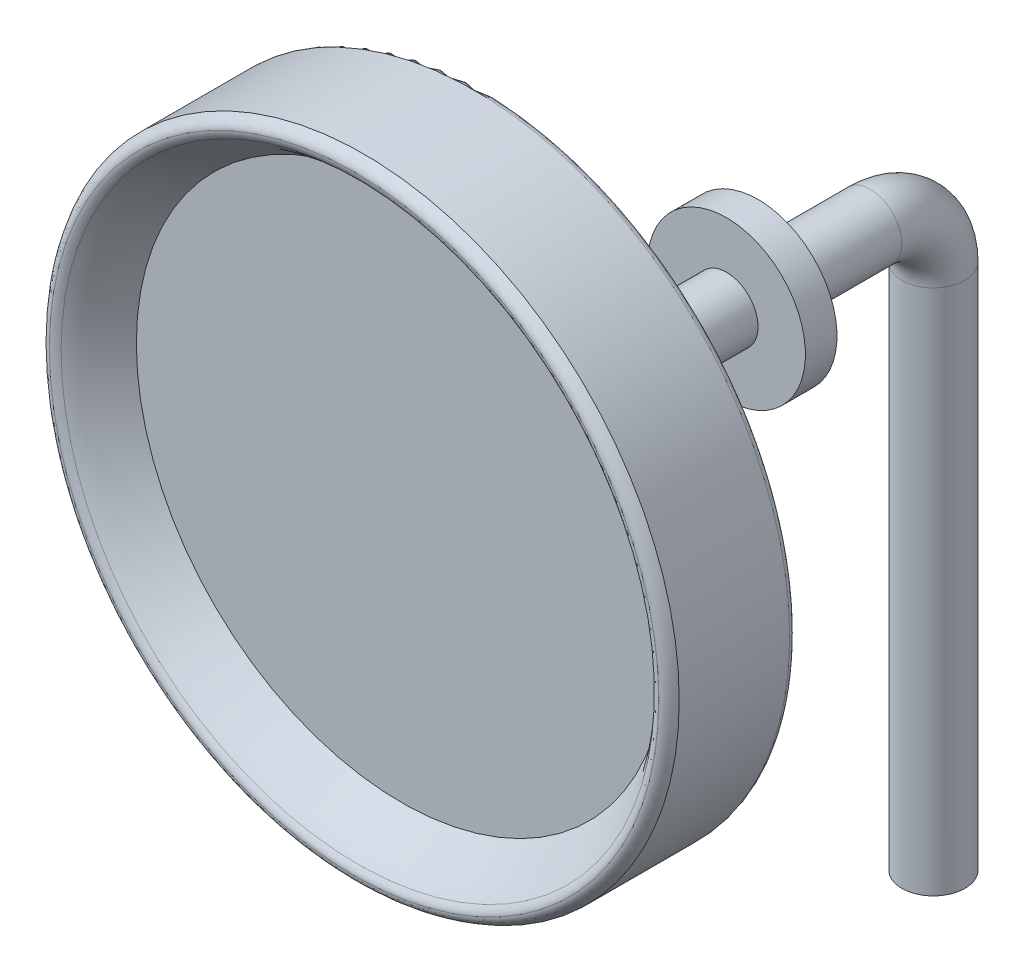
SolidWorks part; units mm, degrees
other "Camera1"
other "Camera2"
other "Camera3"
ref_plane "Front Plane" through (0, 0, 0) normal (0, 0, 1) x (1, 0, 0)
ref_plane "Top Plane" through (0, 0, 0) normal (0, 1, 0) x (1, 0, 0)
ref_plane "Right Plane" through (0, 0, 0) normal (1, 0, 0) x (0, 0, -1)
sketch "Sketch1" plane through (0, 0, 0) normal (1, 0, 0) x (0, 0, -1)
  line L0 (0, 0) -> (50000, 0) construction
  line L2 (7.5, 0) -> (20, 0)
  line L4 (1.5088, 50) -> (19, 50)
  line L5 (20, 0) -> (20, 49)
  line L6 (0, 0) -> (20, 50) construction
  line L7 (0, 50) -> (20, 0) construction
  line L9 (7.5, 0) -> (7.5, 42)
  line L10 (0, 48.2583) -> (0, 48.2932)
  arc A0 (19, 50) -> (20, 49) centre (19, 49) cw
  spline S0 degree 3 poles (1.5088, 50) (-1.703, 48.363) (2.9736, 44.9524) (6.0936, 42.9177) (7.5, 42) knots 0 0 0 0 0.403839 0.72738 0.72738 0.72738 0.72738
  point P7 (10, 25)
  point P8 (0, 45)
  point P9 (20, 45)
  point P10 (0, 42)
  point P11 (20, 42)
  dimension "D3" = 1
  dimension "D1" = 50
  dimension "D2" = 20
revolve "Revolve1" add sketch "Sketch1" angle 360 about L0
sketch "Sketch2" plane through (0, 0, -20) normal (0, 0, -1) x (-1, 0, 0)
  circle A0 centre (0, 0) radius 17.5
  dimension "D1" = 35
sketch "Sketch3" plane through (0, 0, -20) normal (0, 0, -1) x (-1, 0, 0)
  circle A0 centre (0, 0) radius 49 construction
  circle A1 centre (0, 0) radius 49
extrude "Boss-Extrude1" add sketch "Sketch2" along normal blind 2
sketch "Sketch4" plane through (0, 0, -22) normal (0, 0, -1) x (-1, 0, 0)
  circle A0 centre (0, 0) radius 7.5
extrude "Boss-Extrude2" add sketch "Sketch4" along normal blind 5 separate body
sketch "Sketch5" plane through (0, 0, -27) normal (0, 0, -1) x (-1, 0, 0)
  circle A0 centre (0, 0) radius 5
extrude "Boss-Extrude3" add sketch "Sketch5" along normal blind 3
sketch "Sketch6" plane through (0, 0, -30) normal (0, 0, -1) x (-1, 0, 0)
  circle A0 centre (0, 0) radius 7.5
extrude "Boss-Extrude4" add sketch "Sketch6" along normal blind 3 separate body
sketch "Sketch7" plane through (0, 0, -33) normal (0, 0, -1) x (-1, 0, 0)
  circle A0 centre (0, 0) radius 5
extrude "Boss-Extrude5" add sketch "Sketch7" along normal blind 3 separate body
sketch "Sketch8" plane through (0, 0, -36) normal (0, 0, -1) x (-1, 0, 0)
  circle A0 centre (0, 0) radius 7.5
extrude "Boss-Extrude6" add sketch "Sketch8" along normal blind 3
sketch "Sketch9" plane through (0, 0, -39) normal (0, 0, -1) x (-1, 0, 0)
  circle A0 centre (0, 0) radius 5
extrude "Boss-Extrude7" add sketch "Sketch9" along normal blind 3 separate body
sketch "Sketch10" plane through (0, 0, -42) normal (0, 0, -1) x (-1, 0, 0)
  circle A0 centre (0, 0) radius 7.5
extrude "Boss-Extrude8" add sketch "Sketch10" along normal blind 5
sketch "Sketch11" plane through (0, 0, -47) normal (0, 0, -1) x (-1, 0, 0)
  circle A0 centre (0, 0) radius 5
extrude "Boss-Extrude9" add sketch "Sketch11" along normal blind 12 separate body
sketch "Sketch12" plane through (0, 0, -59) normal (0, 0, -1) x (-1, 0, 0)
  circle A0 centre (0, 0) radius 12.5
extrude "Boss-Extrude10" add sketch "Sketch12" along normal blind 5 separate body
sketch "Sketch13" plane through (0, 0, -64) normal (0, 0, -1) x (-1, 0, 0)
  circle A0 centre (0, 0) radius 5
extrude "Boss-Extrude11" add sketch "Sketch13" along normal blind 150 separate body
ref_plane "Plane1" through (0, 0, 0) normal (0, 0, 1) x (1, 0, 0)
sketch "Sketch14" plane through (0, 0, 0) normal (0, 0, 1) x (1, 0, 0)
  circle A0 centre (0, 0) radius 47
split line "Split Line1"
sketch "Sketch15" plane through (0, 0, 0) normal (0, 1, 0) x (1, 0, 0)
  line L1 (-66.6569, 231.4263) -> (60.3087, 231.4263)
  line L2 (-66.6569, 231.4263) -> (-66.6569, 78.4327)
  line L3 (-66.6569, 78.4327) -> (60.3087, 78.4327)
  line L4 (60.3087, 231.4263) -> (60.3087, 78.4327)
extrude "Cut-Extrude1" cut sketch "Sketch15" against normal mid plane 168
sketch "Sketch16" plane through (0, 0, -78.4327) normal (0, 0, -1) x (-1, 0, 0)
  circle A1 centre (0, 0) radius 5
  circle A2 centre (0, 0) radius 5
  dimension "D1" = 0
sketch "Sketch17" plane through (0, 0, 0) normal (1, 0, 0) x (0, 0, -1)
  line L0 (78.4327, 0) -> (81.7736, 0)
  line L1 (78.4327, -5) -> (78.4327, 5) construction
  line L2 (91.7736, -10) -> (91.7736, -93.4177)
  arc A0 (81.7736, 0) -> (91.7736, -10) centre (81.7736, -10) cw
  dimension "D1" = 10
sweep "Sweep1" add profiles "Sketch16" path "Sketch17"
